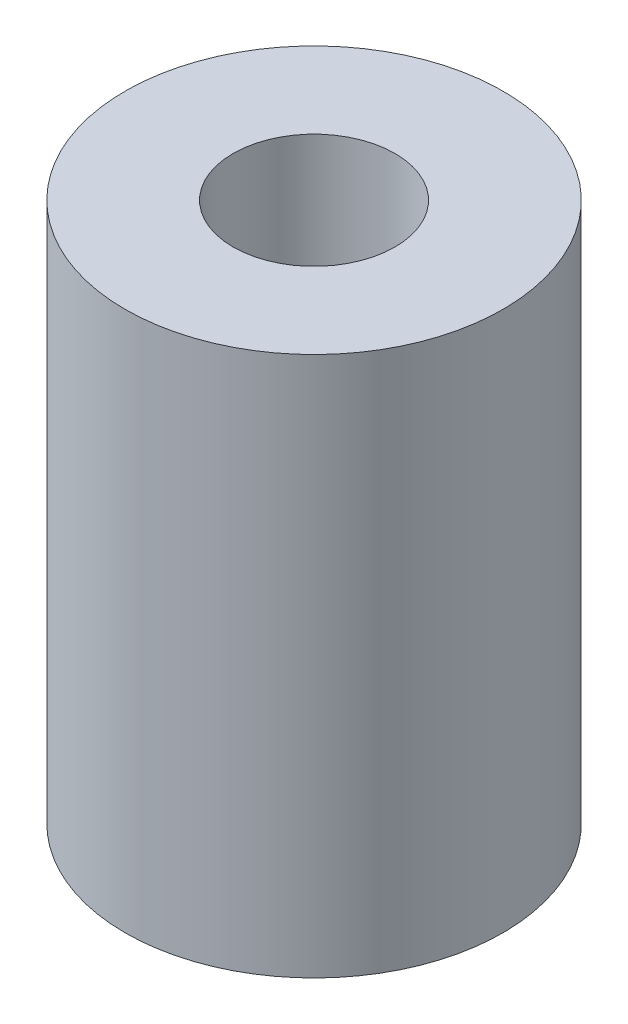
SolidWorks part; units mm, degrees
ref_plane "Front Plane" through (0, 0, 0) normal (0, 0, 1) x (1, 0, 0)
ref_plane "Top Plane" through (0, 0, 0) normal (0, 1, 0) x (1, 0, 0)
ref_plane "Right Plane" through (0, 0, 0) normal (1, 0, 0) x (0, 0, -1)
sketch "Sketch1" plane through (0, 0, 0) normal (0, 1, 0) x (1, 0, 0)
  circle A0 centre (0, 0) radius 3.5
  circle A1 centre (0, 0) radius 1.5
  dimension "D1" = 7
  dimension "D2" = 3
extrude "Boss-Extrude1" add sketch "Sketch1" along normal blind 10
